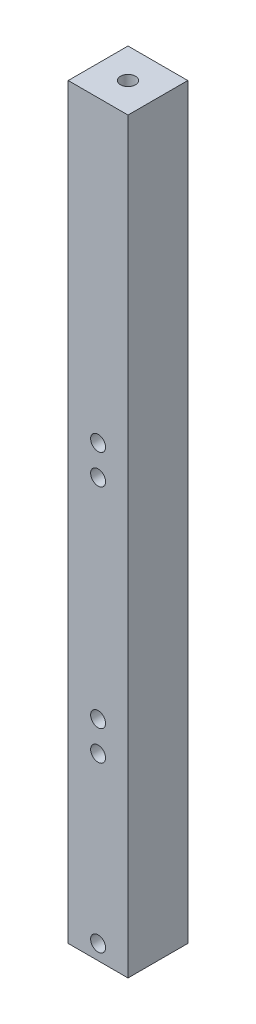
SolidWorks part; units mm, degrees
ref_plane "Front Plane" through (0, 0, 0) normal (0, 0, 1) x (1, 0, 0)
ref_plane "Top Plane" through (0, 0, 0) normal (0, 1, 0) x (1, 0, 0)
ref_plane "Right Plane" through (0, 0, 0) normal (1, 0, 0) x (0, 0, -1)
sketch "Sketch1" plane through (0, 0, 0) normal (0, 1, 0) x (1, 0, 0)
  line L1 (-10, -10) -> (10, -10)
  line L2 (-10, -10) -> (-10, 10)
  line L3 (-10, 10) -> (10, 10)
  line L4 (10, -10) -> (10, 10)
  line L5 (-10, -10) -> (10, 10) construction
  line L6 (-10, 10) -> (10, -10) construction
  circle A0 centre (0, 0) radius 2.5
  point P0 (0, 0)
  dimension "D3" = 5
  dimension "D1" = 20
  dimension "D2" = 20
extrude "Boss-Extrude1" add sketch "Sketch1" along normal blind 250
sketch "Sketch2" plane through (0, 0, 10) normal (0, 0, 1) x (1, 0, 0)
  circle A0 centre (0, 5) radius 2.5
  dimension "D1" = 5
  dimension "D2" = 5
extrude "Cut-Extrude1" cut sketch "Sketch2" against normal blind 100
sketch "Sketch3" plane through (0, 0, 10) normal (0, 0, 1) x (1, 0, 0)
  line L0 (0, -1000) -> (0, 49000) construction
  line L2 (-10, 250) -> (10, 250) construction
  circle A0 centre (0, 60) radius 2.5
  circle A1 centre (0, 140) radius 2.5
  circle A2 centre (0, 70) radius 2.5
  circle A3 centre (0, 150) radius 2.5
  dimension "D1" = 5
  dimension "D3" = 5
  dimension "D5" = 5
  dimension "D6" = 5
  dimension "D7" = 10
  dimension "D8" = 10
  dimension "D4" = 100
  dimension "D2" = 60
extrude "Cut-Extrude2" cut sketch "Sketch3" against normal through all
